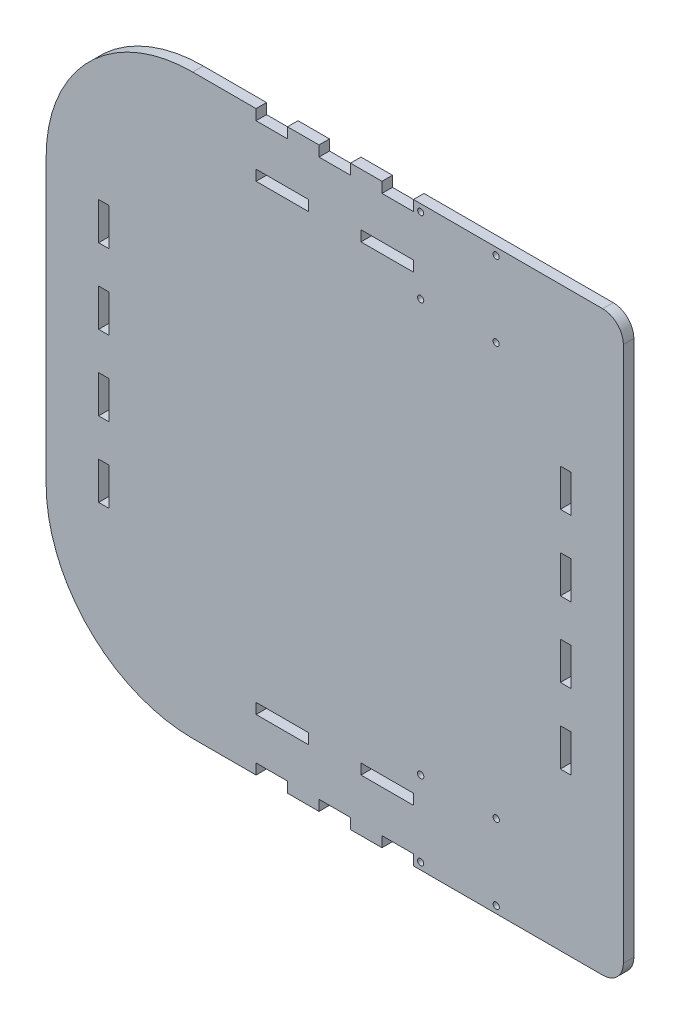
SolidWorks part; units mm, degrees
ref_plane "Front Plane" through (0, 0, 0) normal (0, 0, 1) x (1, 0, 0)
ref_plane "Top Plane" through (0, 0, 0) normal (0, 1, 0) x (1, 0, 0)
ref_plane "Right Plane" through (0, 0, 0) normal (1, 0, 0) x (0, 0, -1)
sketch "Sketch1" plane through (0, 0, 0) normal (0, 0, 1) x (1, 0, 0)
  line L1 (139.7, -139.7) -> (-139.7, -139.7)
  line L2 (139.7, -139.7) -> (139.7, 139.7)
  line L3 (139.7, 139.7) -> (-139.7, 139.7)
  line L4 (-139.7, -139.7) -> (-139.7, 139.7)
  line L5 (139.7, -139.7) -> (-139.7, 139.7) construction
  line L6 (139.7, 139.7) -> (-139.7, -139.7) construction
  point P0 (0, 0)
  dimension "D1" = 279.4
  dimension "D2" = 279.4
extrude "Boss-Extrude1" add sketch "Sketch1" along normal blind 5.08
fillet "Fillet1" radius 70.96 1 edges at (-139.7, 139.7, 2.54)
fillet "Fillet2" radius 70.96 1 edges at (-139.7, -139.7, 2.54)
fillet "Fillet3" radius 10 1 edges at (139.7, 139.7, 2.54)
fillet "Fillet4" radius 10 1 edges at (139.7, -139.7, 2.54)
sketch "Sketch2" plane through (0, 0, 5.08) normal (0, 0, 1) x (1, 0, 0)
  line L0 (-12.7, -109.22) -> (12.7, -109.22) construction
  line L1 (-38.1, -114.3) -> (-12.7, -114.3)
  line L2 (-38.1, -114.3) -> (-38.1, -109.22)
  line L3 (-38.1, -109.22) -> (-12.7, -109.22)
  line L4 (-12.7, -114.3) -> (-12.7, -109.22)
  line L5 (12.7, -114.3) -> (38.1, -114.3)
  line L6 (12.7, -114.3) -> (12.7, -109.22)
  line L7 (12.7, -109.22) -> (38.1, -109.22)
  line L8 (38.1, -114.3) -> (38.1, -109.22)
extrude "Cut-Extrude1" cut sketch "Sketch2" against normal blind 7.62
sketch "Sketch3" plane through (0, 0, 5.08) normal (0, 0, 1) x (1, 0, 0)
  line L0 (-68.74, -139.7) -> (129.7, -139.7) construction
  line L1 (-38.1, -134.62) -> (-22.86, -134.62)
  line L2 (-38.1, -134.62) -> (-38.1, -139.7)
  line L3 (-38.1, -139.7) -> (-22.86, -139.7)
  line L4 (-22.86, -134.62) -> (-22.86, -139.7)
  line L5 (-22.86, -134.62) -> (-22.86, -139.7) construction
  line L6 (7.62, -134.62) -> (7.62, -139.7) construction
  line L7 (-7.62, -134.62) -> (7.62, -134.62)
  line L8 (-7.62, -134.62) -> (-7.62, -139.7)
  line L9 (-7.62, -139.7) -> (7.62, -139.7)
  line L10 (7.62, -134.62) -> (7.62, -139.7)
  line L11 (38.1, -134.62) -> (38.1, -139.7) construction
  line L12 (22.86, -134.62) -> (38.1, -134.62)
  line L13 (22.86, -134.62) -> (22.86, -139.7)
  line L14 (22.86, -139.7) -> (38.1, -139.7)
  line L15 (38.1, -134.62) -> (38.1, -139.7)
extrude "Cut-Extrude2" cut sketch "Sketch3" against normal blind 5.08
sketch "Sketch4" plane through (0, 0, 5.08) normal (0, 0, 1) x (1, 0, 0)
  line L0 (129.7, 139.7) -> (-68.74, 139.7) construction
  line L1 (-38.1, 109.22) -> (-12.7, 109.22)
  line L2 (-38.1, 109.22) -> (-38.1, 114.3)
  line L3 (-38.1, 114.3) -> (-12.7, 114.3)
  line L4 (-12.7, 109.22) -> (-12.7, 114.3)
  line L5 (12.7, 109.22) -> (38.1, 109.22)
  line L6 (12.7, 109.22) -> (12.7, 114.3)
  line L7 (12.7, 114.3) -> (38.1, 114.3)
  line L8 (38.1, 109.22) -> (38.1, 114.3)
  line L9 (-38.1, 134.62) -> (-22.86, 134.62)
  line L10 (-38.1, 134.62) -> (-38.1, 139.7)
  line L11 (-38.1, 139.7) -> (-22.86, 139.7)
  line L12 (-22.86, 134.62) -> (-22.86, 139.7)
  line L13 (-22.86, 139.7) -> (-22.86, 134.62) construction
  line L14 (7.62, 139.7) -> (7.62, 134.62) construction
  line L15 (-7.62, 134.62) -> (7.62, 134.62)
  line L16 (-7.62, 134.62) -> (-7.62, 139.7)
  line L17 (-7.62, 139.7) -> (7.62, 139.7)
  line L18 (7.62, 134.62) -> (7.62, 139.7)
  line L20 (22.86, 134.62) -> (38.1, 134.62)
  line L21 (22.86, 134.62) -> (22.86, 139.7)
  line L22 (22.86, 139.7) -> (38.1, 139.7)
  line L23 (38.1, 134.62) -> (38.1, 139.7)
extrude "Cut-Extrude3" cut sketch "Sketch4" against normal blind 5.08
sketch "Sketch5" plane through (0, 0, 0) normal (0, 0, -1) x (-1, 0, 0)
  line L1 (114.3, -63.5) -> (109.22, -63.5)
  line L2 (114.3, -63.5) -> (114.3, -45.3571)
  line L3 (114.3, -45.3571) -> (109.22, -45.3571)
  line L4 (109.22, -63.5) -> (109.22, -45.3571)
  line L5 (114.3, -27.2143) -> (109.22, -27.2143)
  line L6 (114.3, -27.2143) -> (114.3, -9.0714)
  line L7 (114.3, -9.0714) -> (109.22, -9.0714)
  line L8 (109.22, -27.2143) -> (109.22, -9.0714)
  line L9 (114.3, 9.0714) -> (109.22, 9.0714)
  line L10 (114.3, 9.0714) -> (114.3, 27.2143)
  line L11 (114.3, 27.2143) -> (109.22, 27.2143)
  line L12 (109.22, 9.0714) -> (109.22, 27.2143)
  line L13 (114.3, 45.3571) -> (109.22, 45.3571)
  line L14 (114.3, 45.3571) -> (114.3, 63.5)
  line L15 (114.3, 63.5) -> (109.22, 63.5)
  line L16 (109.22, 45.3571) -> (109.22, 63.5)
  line L17 (-109.22, -63.5) -> (-114.3, -63.5)
  line L18 (-109.22, -63.5) -> (-109.22, -45.3571)
  line L19 (-109.22, -45.3571) -> (-114.3, -45.3571)
  line L20 (-114.3, -63.5) -> (-114.3, -45.3571)
  line L21 (-109.22, -27.2143) -> (-114.3, -27.2143)
  line L22 (-109.22, -27.2143) -> (-109.22, -9.0714)
  line L23 (-109.22, -9.0714) -> (-114.3, -9.0714)
  line L24 (-114.3, -27.2143) -> (-114.3, -9.0714)
  line L25 (-109.22, 9.0714) -> (-114.3, 9.0714)
  line L26 (-109.22, 9.0714) -> (-109.22, 27.2143)
  line L27 (-109.22, 27.2143) -> (-114.3, 27.2143)
  line L28 (-114.3, 9.0714) -> (-114.3, 27.2143)
  line L29 (-109.22, 45.3571) -> (-114.3, 45.3571)
  line L30 (-109.22, 45.3571) -> (-109.22, 63.5)
  line L31 (-109.22, 63.5) -> (-114.3, 63.5)
  line L32 (-114.3, 45.3571) -> (-114.3, 63.5)
extrude "Cut-Extrude4" cut sketch "Sketch5" against normal blind 5.08
sketch "Sketch7" plane through (0, 0, 5.08) normal (0, 0, 1) x (1, 0, 0)
  line L0 (41.6, -137.7) -> (41.6, -98) construction
  line L1 (41.6, -98) -> (78.1, -98) construction
  line L2 (78.1, -98) -> (78.1, -137.7) construction
  line L3 (78.1, -137.7) -> (41.6, -137.7) construction
  line L4 (78.1, -101.2) -> (78.1, -98) construction
  line L5 (78.1, -101.2) -> (78.1, -98) construction
  point P9 (0, 0)
  point P11 (0, 0)
sketch "Sketch9" plane through (0, 0, 0) normal (0, 0, -1) x (-1, 0, 0)
  circle A0 centre (-78.1743, -99.7839) radius 1.5217
  circle A1 centre (-41.589, -99.7839) radius 1.5244
  circle A2 centre (-41.589, -136.3059) radius 1.4831
  circle A3 centre (-78.1743, -136.3059) radius 1.5099
extrude "Cut-Extrude5" cut sketch "Sketch9" against normal blind 5.08
sketch "Sketch10" plane through (0, 0, 0) normal (0, 0, -1) x (-1, 0, 0)
  circle A0 centre (-78.1127, 136.2145) radius 1.4964
  circle A1 centre (-78.1127, 99.7153) radius 1.496
  circle A2 centre (-41.5906, 99.7153) radius 1.4993
  circle A3 centre (-41.5906, 136.2145) radius 1.4407
extrude "Cut-Extrude6" cut sketch "Sketch10" against normal blind 5.08
equation "\"foamcore\"= .1in"
equation "\"MDF\"= .2in"
equation "\"GMaterial\"= \"MDF\""
equation "\"D1@Boss-Extrude1\"=\"GMaterial\""
equation "\"D1@Cut-Extrude2\"=\"GMaterial\""
equation "\"D1@Cut-Extrude3\"=\"GMaterial\""
equation "\"D1@Cut-Extrude4\"=\"GMaterial\""
equation "\"D1@Cut-Extrude5\"=\"GMaterial\""
equation "\"D1@Cut-Extrude6\"=\"GMaterial\""
